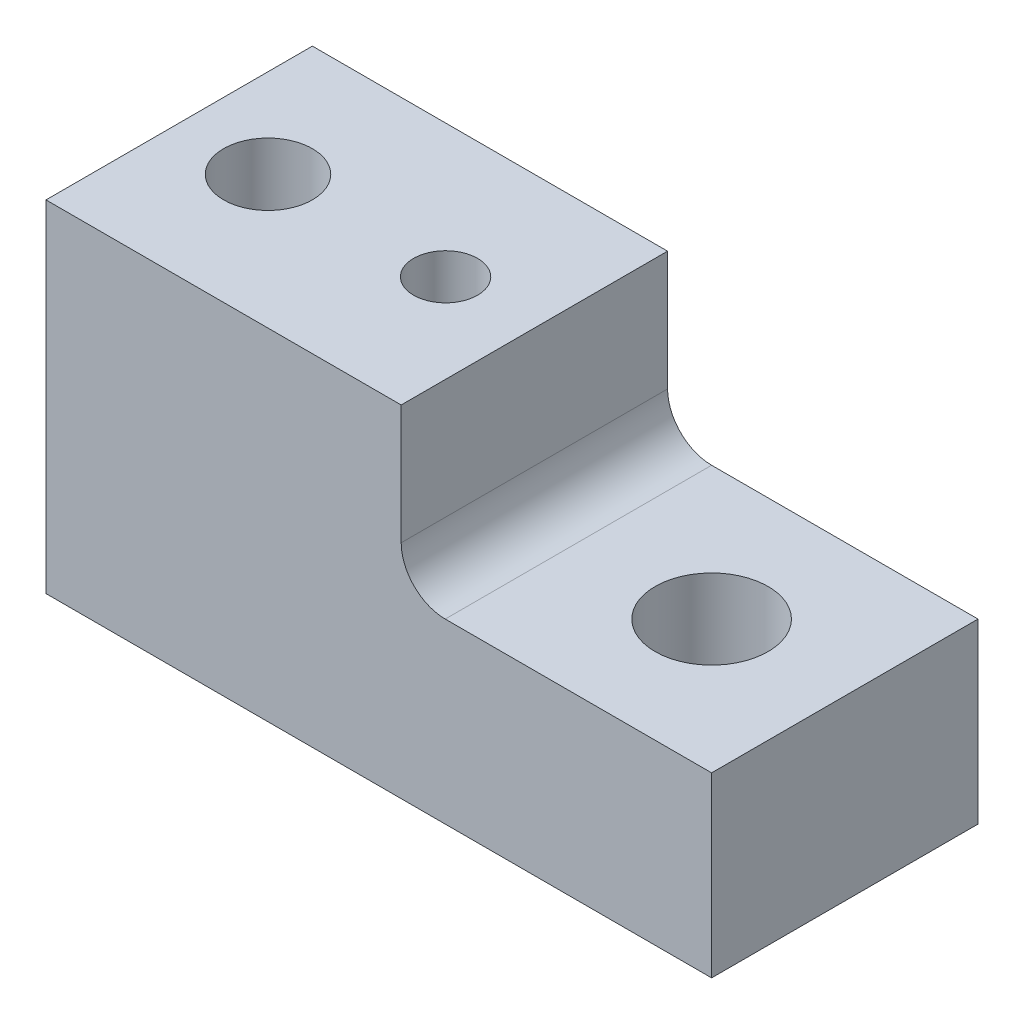
SolidWorks part; units mm, degrees
ref_plane "Front Plane" through (0, 0, 0) normal (0, 0, 1) x (1, 0, 0)
ref_plane "Top Plane" through (0, 0, 0) normal (0, 1, 0) x (1, 0, 0)
ref_plane "Right Plane" through (0, 0, 0) normal (1, 0, 0) x (0, 0, -1)
sketch "Sketch1" plane through (0, 0, 0) normal (0, 1, 0) x (1, 0, 0)
  line L0 (11.8999, -4.7625) -> (11.8999, 4.7625)
  line L1 (11.8999, -4.7625) -> (-11.8999, -4.7625)
  line L2 (11.8999, 4.7625) -> (-11.8999, 4.7625)
  line L3 (-11.8999, -4.7625) -> (-11.8999, 4.7625)
  line L4 (11.8999, -4.7625) -> (-11.8999, 4.7625) construction
  line L5 (11.8999, 4.7625) -> (-11.8999, -4.7625) construction
  point P1 (0, 0)
  dimension "D1" = 23.7998
  dimension "D2" = 9.525
extrude "Boss-Extrude1" add sketch "Sketch1" along normal blind 12.192
sketch "Sketch2" plane through (0, 12.192, 0) normal (0, 1, 0) x (1, 0, 0)
  line L5 (11.8999, -4.7625) -> (0.8001, -4.7625)
  line L6 (11.8999, -4.7625) -> (11.8999, 4.7625)
  line L7 (11.8999, 4.7625) -> (0.8001, 4.7625)
  line L8 (0.8001, -4.7625) -> (0.8001, 4.7625)
  dimension "D1" = 11.0998
extrude "Cut-Extrude1" cut sketch "Sketch2" against normal blind 5.842
fillet "Fillet1" radius 1.5748 1 edges at (0.8001, 6.35, 0)
hole_wizard "#4-40 Tapped Hole5" positions "3DSketch1" profile "Sketch6" tap size "#4-40" standard "ANSI Inch"
sketch3d "3DSketch1"
  line L0 (0.8001, 12.192, -4.7625) -> (0.8001, 12.192, 4.7625) construction
  line L1 (0.8001, 12.192, -4.7625) -> (-11.8999, 12.192, -4.7625) construction
  point P18 (-2.3749, 12.192, 0)
  dimension "D1" = 3.175
  dimension "D2" = 4.7625
sketch "Sketch6" plane through (-2.3749, 12.192, 0) normal (1, 0, 0) x (0, 0, 1)
  line L0 (0, 0) -> (0, 7.0292)
  line L1 (0, 7.0292) -> (1.1303, 6.35)
  line L2 (1.1303, 6.35) -> (1.1303, 0)
  line L5 (1.1303, 0) -> (0, 0)
  line L10 (0, 7.0292) -> (-1.1303, 6.35) construction
  line L11 (0, -6.35) -> (0, 107.95) construction
  dimension "Tap Drill Dia." = 2.2606
  dimension "Tap Drill Depth" = 6.35
  dimension "Drill Angle" = 118
cosmetic thread "Hole Thread2" parameters "D1"=6.35, "D2"=2.8448
sketch "Sketch4" plane through (0, 12.192, 0) normal (0, 1, 0) x (1, 0, 0)
  line L0 (11.8999, -4.7625) -> (11.8999, 4.7625) construction
  line L1 (0.8001, 4.7625) -> (-11.8999, 4.7625) construction
  circle A0 centre (-8.7249, 0) radius 1.5875
  circle A2 centre (-2.3749, 0) radius 1.143
  point P6 (-2.3749, 0)
  dimension "D3" = 3.175
  dimension "D5" = 2.286
  dimension "D1" = 20.6248
  dimension "D2" = 4.7625
  dimension "D4" = 14.2748
extrude "Cut-Extrude2" cut sketch "Sketch4" against normal through all
hole_wizard "#10-32 Tapped Hole1" positions "Sketch7" profile "Sketch9" tap size "#10-32" standard "ANSI Inch" end condition through all
sketch "Sketch7" plane through (0, 6.35, 0) normal (0, 1, 0) x (1, 0, 0)
  line L0 (11.8999, -4.7625) -> (11.8999, 4.7625) construction
  line L1 (2.3749, -4.7625) -> (11.8999, -4.7625) construction
  point P0 (7.1374, 0)
  dimension "D1" = 4.7625
  dimension "D2" = 4.7625
sketch "Sketch9" plane through (7.1374, 6.35, 0) normal (1, 0, 0) x (0, 0, 1)
  line L0 (0, 0) -> (0, 6.35)
  line L1 (0, 6.35) -> (2.0193, 6.35)
  line L2 (2.0193, 6.35) -> (2.0193, 0)
  line L5 (2.0193, 0) -> (0, 0)
  line L11 (0, -6.35) -> (0, 107.95) construction
  dimension "Thru Tap Drill Dia." = 4.0386
  dimension "Thru Tap Drill Depth" = 6.35
cosmetic thread "Hole Thread3" parameters "D2"=4.826
